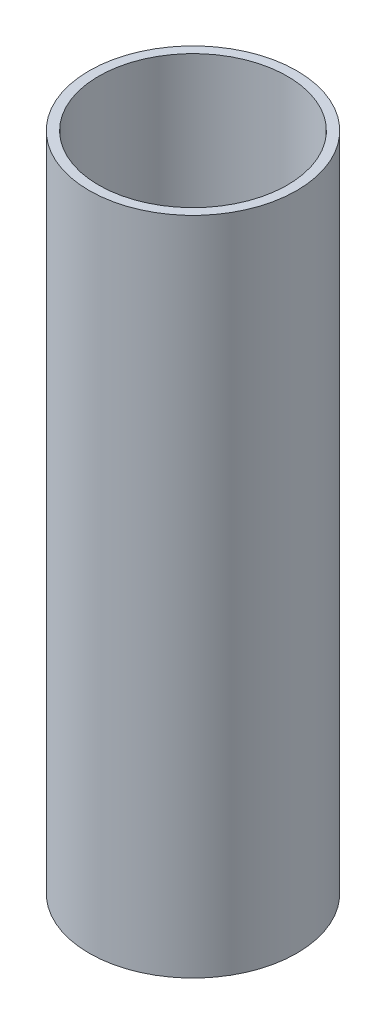
SolidWorks part; units mm, degrees
material "PMMA"
ref_plane "Alzado" through (0, 0, 0) normal (0, 0, 1) x (1, 0, 0)
ref_plane "Planta" through (0, 0, 0) normal (0, 1, 0) x (1, 0, 0)
ref_plane "Vista lateral" through (0, 0, 0) normal (1, 0, 0) x (0, 0, -1)
sketch "Croquis1" plane through (0, 0, 0) normal (0, 1, 0) x (1, 0, 0)
  circle A0 centre (0, 0) radius 55
  dimension "D1" = 110
extrude "Saliente-Extruir1" add sketch "Croquis1" along normal blind 350
sketch "Croquis3" plane through (0, 350, 0) normal (0, 1, 0) x (1, 0, 0)
  circle A2 centre (0, 0) radius 50
  circle A3 centre (0, 0) radius 50
  dimension "D1" = 5
extrude "Cortar-Extruir1" cut sketch "Croquis3" against normal up to surface (350 mm away) up to face at (0, 0, 55)
